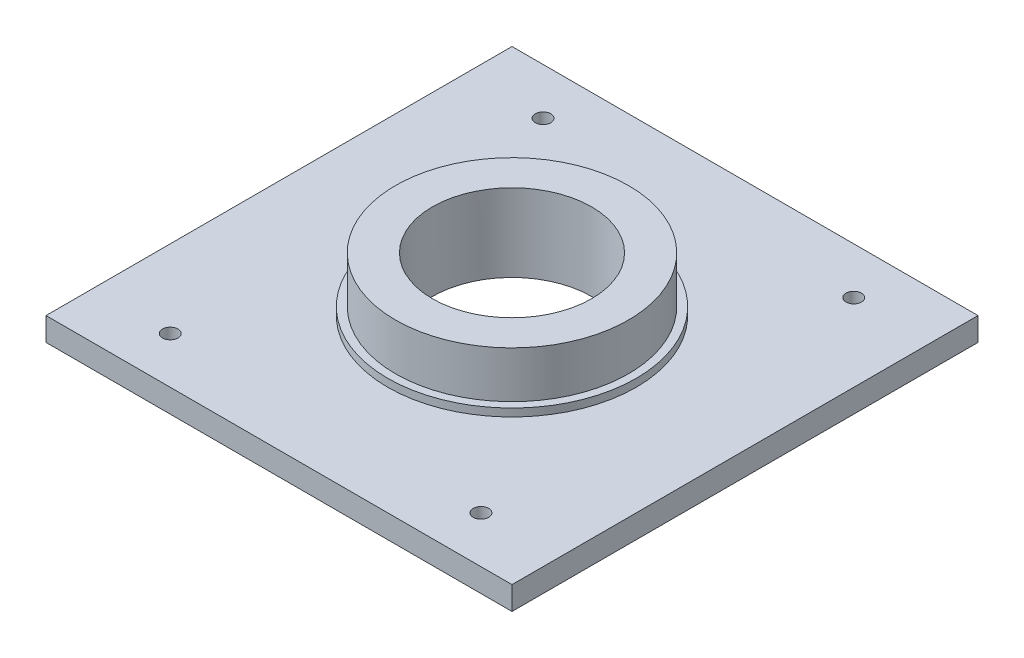
SolidWorks part; units mm, degrees
ref_plane "Front Plane" through (0, 0, 0) normal (0, 0, 1) x (1, 0, 0)
ref_plane "Top Plane" through (0, 0, 0) normal (0, 1, 0) x (1, 0, 0)
ref_plane "Right Plane" through (0, 0, 0) normal (1, 0, 0) x (0, 0, -1)
sketch "Sketch1" plane through (0, 0, 0) normal (0, 1, 0) x (1, 0, 0)
  line L1 (30, -30) -> (-30, -30)
  line L2 (30, -30) -> (30, 30)
  line L3 (30, 30) -> (-30, 30)
  line L4 (-30, -30) -> (-30, 30)
  line L5 (30, -30) -> (-30, 30) construction
  line L6 (30, 30) -> (-30, -30) construction
  point P0 (0, 0)
extrude "Boss-Extrude1" add sketch "Sketch1" along normal blind 3
sketch "Sketch2" plane through (0, 3, 0) normal (0, 1, 0) x (1, 0, 0)
  line L0 (-7, 0) -> (-6.6, 0) construction
  line L1 (-7, 4) -> (-5.2498, 4)
  line L2 (-7, -4) -> (-5.2498, -4)
  line L3 (0, -7) -> (0, -6.6) construction
  line L4 (-4, -7) -> (-4, -5.2498)
  line L5 (4, -7) -> (4, -5.2498)
  line L6 (5.2498, 4) -> (7, 4)
  line L7 (-4, 5.2498) -> (-4, 7)
  line L8 (6.6, 0) -> (7, 0) construction
  line L9 (0, 6.6) -> (0, 7) construction
  line L10 (5.2498, -4) -> (7, -4)
  line L11 (4, 5.2498) -> (4, 7)
  arc A0 (-4, 5.2498) -> (-5.2498, 4) centre (0, 0) ccw
  arc A2 (-7, 4) -> (-7, -4) centre (-7, 0) ccw
  arc A3 (7, -4) -> (7, 4) centre (7, 0) ccw
  arc A4 (-4, -7) -> (4, -7) centre (0, -7) ccw
  arc A5 (4, 7) -> (-4, 7) centre (0, 7) ccw
  arc A6 (5.2498, 4) -> (4, 5.2498) centre (0, 0) ccw
  arc A7 (4, -5.2498) -> (5.2498, -4) centre (0, 0) ccw
  arc A8 (-5.2498, -4) -> (-4, -5.2498) centre (0, 0) ccw
  point P5 (0, 0)
  point P11 (0, 0)
extrude "Cut-Extrude1" [suppressed] cut sketch "Sketch2" against normal through all
sketch "Sketch3" plane through (0, 3, 0) normal (0, 1, 0) x (1, 0, 0)
  circle A0 centre (-20, 24) radius 1
  circle A1 centre (20, 24) radius 1
  circle A2 centre (-20, -24) radius 1
  circle A3 centre (20, -24) radius 1
extrude "Cut-Extrude3" cut sketch "Sketch3" against normal through all
sketch "Sketch4" plane through (0, 0, 0) normal (0, -1, 0) x (1, 0, 0)
  line L0 (-20, 24) -> (20, -24) construction
  line L1 (-20, -24) -> (20, 24) construction
  point P11 (0, 0)
sketch "Sketch5" plane through (0, 0, 0) normal (0, -1, 0) x (1, 0, 0)
  circle A0 centre (0, 0) radius 10.25
extrude "Cut-Extrude4" cut sketch "Sketch5" against normal through all
sketch "Sketch6" plane through (0, 3, 0) normal (0, 1, 0) x (1, 0, 0)
  circle A0 centre (0, 0) radius 16
  circle A1 centre (0, 0) radius 10.25
extrude "Boss-Extrude2" add sketch "Sketch6" along normal blind 1
sketch "Sketch7" plane through (0, 3, 0) normal (0, 1, 0) x (1, 0, 0)
  line L0 (-20, 24) -> (20, -24) construction
  circle A0 centre (0, 0) radius 15
  circle A1 centre (0, 0) radius 10.25
extrude "Boss-Extrude3" add sketch "Sketch7" along normal blind 7
